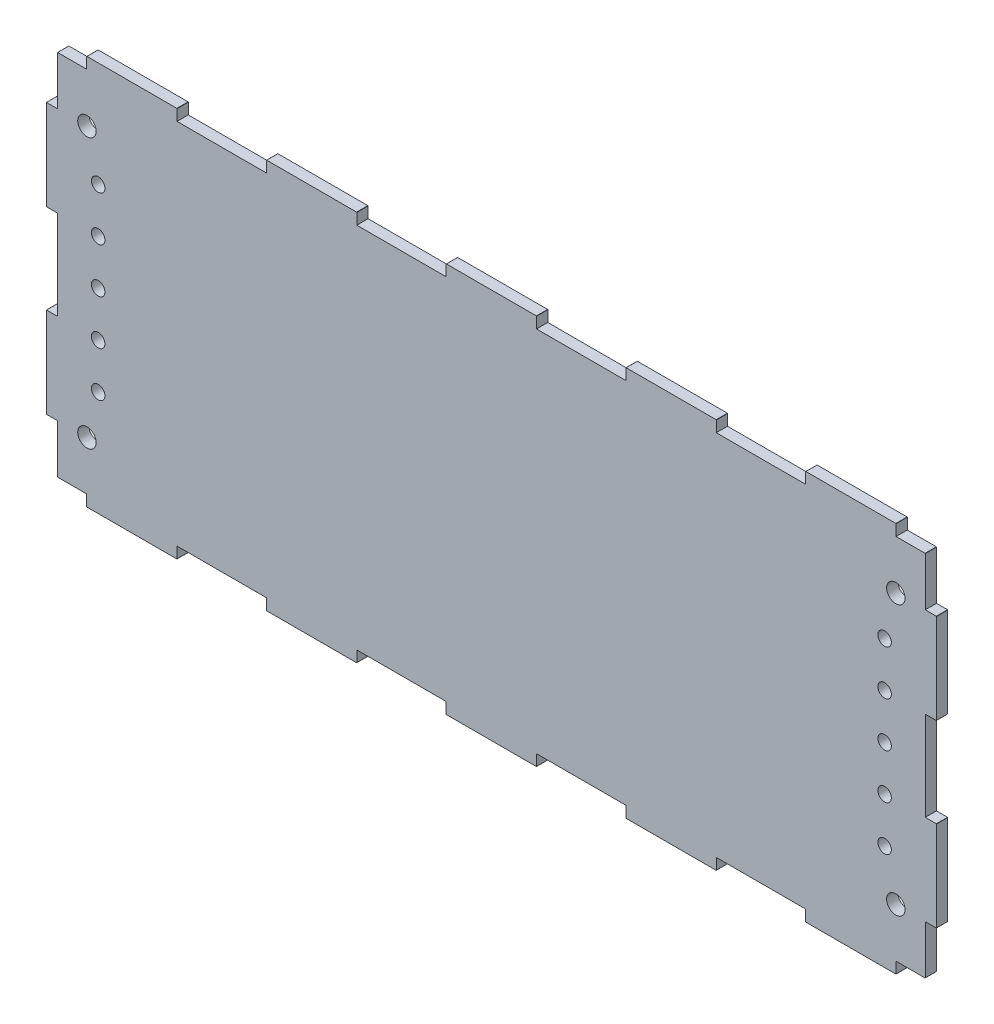
SolidWorks part; units mm, degrees
material "Acrylic (Medium-high impact)"
ref_plane "Front Plane" through (0, 0, 0) normal (0, 0, 1) x (1, 0, 0)
ref_plane "Top Plane" through (0, 0, 0) normal (0, 1, 0) x (1, 0, 0)
ref_plane "Right Plane" through (0, 0, 0) normal (1, 0, 0) x (0, 0, -1)
sketch "Model" plane through (0, 0, 0) normal (0, 0, 1) x (1, 0, 0)
  line L0 (-139.94, -86.83) -> (-139.93, -86.82)
  line L1 (-139.93, -86.82) -> (-139.92, -86.8)
  line L2 (-139.92, -86.8) -> (-139.91, -86.79)
  line L3 (-139.91, -86.79) -> (-139.9, -86.77)
  line L4 (-139.9, -86.77) -> (-139.9, -81.85)
  line L5 (-139.9, -81.85) -> (-100.1, -81.85)
  line L6 (-100.1, -81.85) -> (-100.1, -86.77)
  line L7 (-100.1, -86.77) -> (-100.08, -86.81)
  line L8 (-100.08, -86.81) -> (-100.07, -86.82)
  line L9 (-100.07, -86.82) -> (-100.05, -86.83)
  line L10 (-100.05, -86.83) -> (-100.04, -86.84)
  line L11 (-100.04, -86.84) -> (-100.02, -86.85)
  line L12 (-100.02, -86.85) -> (-59.98, -86.85)
  line L13 (-59.98, -86.85) -> (-59.94, -86.83)
  line L14 (-59.94, -86.83) -> (-59.93, -86.82)
  line L15 (-59.93, -86.82) -> (-59.92, -86.8)
  line L16 (-59.92, -86.8) -> (-59.91, -86.79)
  line L17 (-59.91, -86.79) -> (-59.9, -86.77)
  line L18 (-59.9, -86.77) -> (-59.9, -81.85)
  line L19 (-59.9, -81.85) -> (-20.1, -81.85)
  line L20 (-20.1, -81.85) -> (-20.1, -86.77)
  line L21 (-20.1, -86.77) -> (-20.08, -86.81)
  line L22 (-20.08, -86.81) -> (-20.07, -86.82)
  line L23 (-20.07, -86.82) -> (-20.05, -86.83)
  line L24 (-20.05, -86.83) -> (-20.04, -86.84)
  line L25 (-20.04, -86.84) -> (-20.02, -86.85)
  line L26 (-20.02, -86.85) -> (20.02, -86.85)
  line L27 (20.02, -86.85) -> (20.06, -86.83)
  line L28 (20.06, -86.83) -> (20.07, -86.82)
  line L29 (20.07, -86.82) -> (20.08, -86.8)
  line L30 (20.08, -86.8) -> (20.09, -86.79)
  line L31 (20.09, -86.79) -> (20.1, -86.77)
  line L32 (20.1, -86.77) -> (20.1, -81.85)
  line L33 (20.1, -81.85) -> (59.9, -81.85)
  line L34 (59.9, -81.85) -> (59.9, -86.77)
  line L35 (59.9, -86.77) -> (59.92, -86.81)
  line L36 (59.92, -86.81) -> (59.93, -86.82)
  line L37 (59.93, -86.82) -> (59.95, -86.83)
  line L38 (59.95, -86.83) -> (59.96, -86.84)
  line L39 (59.96, -86.84) -> (59.98, -86.85)
  line L40 (59.98, -86.85) -> (100.02, -86.85)
  line L41 (100.02, -86.85) -> (100.06, -86.83)
  line L42 (100.06, -86.83) -> (100.07, -86.82)
  line L43 (100.07, -86.82) -> (100.08, -86.8)
  line L44 (100.08, -86.8) -> (100.09, -86.79)
  line L45 (100.09, -86.79) -> (100.1, -86.77)
  line L46 (100.1, -86.77) -> (100.1, -81.85)
  line L47 (100.1, -81.85) -> (139.9, -81.85)
  line L48 (139.9, -81.85) -> (139.9, -86.77)
  line L49 (139.9, -86.77) -> (139.92, -86.81)
  line L50 (139.92, -86.81) -> (139.93, -86.82)
  line L51 (139.93, -86.82) -> (139.95, -86.83)
  line L52 (139.95, -86.83) -> (139.96, -86.84)
  line L53 (139.96, -86.84) -> (139.98, -86.85)
  line L54 (139.98, -86.85) -> (180.02, -86.85)
  line L55 (180.02, -86.85) -> (180.06, -86.83)
  line L56 (180.06, -86.83) -> (180.07, -86.82)
  line L57 (180.07, -86.82) -> (180.08, -86.8)
  line L58 (180.08, -86.8) -> (180.09, -86.79)
  line L59 (180.09, -86.79) -> (180.1, -86.77)
  line L60 (180.1, -86.77) -> (180.1, -81.85)
  line L61 (180.1, -81.85) -> (193.02, -81.85)
  line L62 (193.02, -81.85) -> (193.06, -81.83)
  line L63 (193.06, -81.83) -> (193.07, -81.82)
  line L64 (193.07, -81.82) -> (193.08, -81.8)
  line L65 (193.08, -81.8) -> (193.09, -81.79)
  line L66 (193.09, -81.79) -> (193.1, -81.77)
  line L67 (193.1, -81.77) -> (193.1, -60.1)
  line L68 (193.1, -60.1) -> (198.02, -60.1)
  line L69 (198.02, -60.1) -> (198.06, -60.08)
  line L70 (198.06, -60.08) -> (198.07, -60.07)
  line L71 (198.07, -60.07) -> (198.08, -60.05)
  line L72 (198.08, -60.05) -> (198.09, -60.04)
  line L73 (198.09, -60.04) -> (198.1, -60.02)
  line L74 (198.1, -60.02) -> (198.1, -19.98)
  line L75 (198.1, -19.98) -> (198.08, -19.94)
  line L76 (198.08, -19.94) -> (198.07, -19.93)
  line L77 (198.07, -19.93) -> (198.05, -19.92)
  line L78 (198.05, -19.92) -> (198.04, -19.91)
  line L79 (198.04, -19.91) -> (198.02, -19.9)
  line L80 (198.02, -19.9) -> (193.1, -19.9)
  line L81 (193.1, -19.9) -> (193.1, 19.9)
  line L82 (193.1, 19.9) -> (198.02, 19.9)
  line L83 (198.02, 19.9) -> (198.06, 19.92)
  line L84 (198.06, 19.92) -> (198.07, 19.93)
  line L85 (198.07, 19.93) -> (198.08, 19.95)
  line L86 (198.08, 19.95) -> (198.09, 19.96)
  line L87 (198.09, 19.96) -> (198.1, 19.98)
  line L88 (198.1, 19.98) -> (198.1, 60.02)
  line L89 (198.1, 60.02) -> (198.08, 60.06)
  line L90 (198.08, 60.06) -> (198.07, 60.07)
  line L91 (198.07, 60.07) -> (198.05, 60.08)
  line L92 (198.05, 60.08) -> (198.04, 60.09)
  line L93 (198.04, 60.09) -> (198.02, 60.1)
  line L94 (198.02, 60.1) -> (193.1, 60.1)
  line L95 (193.1, 60.1) -> (193.1, 81.77)
  line L96 (193.1, 81.77) -> (193.08, 81.81)
  line L97 (193.08, 81.81) -> (193.07, 81.82)
  line L98 (193.07, 81.82) -> (193.05, 81.83)
  line L99 (193.05, 81.83) -> (193.04, 81.84)
  line L100 (193.04, 81.84) -> (193.02, 81.85)
  line L101 (193.02, 81.85) -> (180.1, 81.85)
  line L102 (180.1, 81.85) -> (180.1, 86.77)
  line L103 (180.1, 86.77) -> (180.08, 86.81)
  line L104 (180.08, 86.81) -> (180.07, 86.82)
  line L105 (180.07, 86.82) -> (180.05, 86.83)
  line L106 (180.05, 86.83) -> (180.04, 86.84)
  line L107 (180.04, 86.84) -> (180.02, 86.85)
  line L108 (180.02, 86.85) -> (139.98, 86.85)
  line L109 (139.98, 86.85) -> (139.94, 86.83)
  line L110 (139.94, 86.83) -> (139.93, 86.82)
  line L111 (139.93, 86.82) -> (139.92, 86.8)
  line L112 (139.92, 86.8) -> (139.91, 86.79)
  line L113 (139.91, 86.79) -> (139.9, 86.77)
  line L114 (139.9, 86.77) -> (139.9, 81.85)
  line L115 (139.9, 81.85) -> (100.1, 81.85)
  line L116 (100.1, 81.85) -> (100.1, 86.77)
  line L117 (100.1, 86.77) -> (100.08, 86.81)
  line L118 (100.08, 86.81) -> (100.07, 86.82)
  line L119 (100.07, 86.82) -> (100.05, 86.83)
  line L120 (100.05, 86.83) -> (100.04, 86.84)
  line L121 (100.04, 86.84) -> (100.02, 86.85)
  line L122 (100.02, 86.85) -> (59.98, 86.85)
  line L123 (59.98, 86.85) -> (59.94, 86.83)
  line L124 (59.94, 86.83) -> (59.93, 86.82)
  line L125 (59.93, 86.82) -> (59.92, 86.8)
  line L126 (59.92, 86.8) -> (59.91, 86.79)
  line L127 (59.91, 86.79) -> (59.9, 86.77)
  line L128 (59.9, 86.77) -> (59.9, 81.85)
  line L129 (59.9, 81.85) -> (20.1, 81.85)
  line L130 (20.1, 81.85) -> (20.1, 86.77)
  line L131 (20.1, 86.77) -> (20.08, 86.81)
  line L132 (20.08, 86.81) -> (20.07, 86.82)
  line L133 (20.07, 86.82) -> (20.05, 86.83)
  line L134 (20.05, 86.83) -> (20.04, 86.84)
  line L135 (20.04, 86.84) -> (20.02, 86.85)
  line L136 (20.02, 86.85) -> (-20.02, 86.85)
  line L137 (-20.02, 86.85) -> (-20.06, 86.83)
  line L138 (-20.06, 86.83) -> (-20.07, 86.82)
  line L139 (-20.07, 86.82) -> (-20.08, 86.8)
  line L140 (-20.08, 86.8) -> (-20.09, 86.79)
  line L141 (-20.09, 86.79) -> (-20.1, 86.77)
  line L142 (-20.1, 86.77) -> (-20.1, 81.85)
  line L143 (-20.1, 81.85) -> (-59.9, 81.85)
  line L144 (-59.9, 81.85) -> (-59.9, 86.77)
  line L145 (-59.9, 86.77) -> (-59.92, 86.81)
  line L146 (-59.92, 86.81) -> (-59.93, 86.82)
  line L147 (-59.93, 86.82) -> (-59.95, 86.83)
  line L148 (-59.95, 86.83) -> (-59.96, 86.84)
  line L149 (-59.96, 86.84) -> (-59.98, 86.85)
  line L150 (-59.98, 86.85) -> (-100.02, 86.85)
  line L151 (-100.02, 86.85) -> (-100.06, 86.83)
  line L152 (-100.06, 86.83) -> (-100.07, 86.82)
  line L153 (-100.07, 86.82) -> (-100.08, 86.8)
  line L154 (-100.08, 86.8) -> (-100.09, 86.79)
  line L155 (-100.09, 86.79) -> (-100.1, 86.77)
  line L156 (-100.1, 86.77) -> (-100.1, 81.85)
  line L157 (-100.1, 81.85) -> (-139.9, 81.85)
  line L158 (-139.9, 81.85) -> (-139.9, 86.77)
  line L159 (-139.9, 86.77) -> (-139.92, 86.81)
  line L160 (-139.92, 86.81) -> (-139.93, 86.82)
  line L161 (-139.93, 86.82) -> (-139.95, 86.83)
  line L162 (-139.95, 86.83) -> (-139.96, 86.84)
  line L163 (-139.96, 86.84) -> (-139.98, 86.85)
  line L164 (-139.98, 86.85) -> (-180.02, 86.85)
  line L165 (-180.02, 86.85) -> (-180.06, 86.83)
  line L166 (-180.06, 86.83) -> (-180.07, 86.82)
  line L167 (-180.07, 86.82) -> (-180.08, 86.8)
  line L168 (-180.08, 86.8) -> (-180.09, 86.79)
  line L169 (-180.09, 86.79) -> (-180.1, 86.77)
  line L170 (-180.1, 86.77) -> (-180.1, 81.85)
  line L171 (-180.1, 81.85) -> (-193.02, 81.85)
  line L172 (-193.02, 81.85) -> (-193.06, 81.83)
  line L173 (-193.06, 81.83) -> (-193.07, 81.82)
  line L174 (-193.07, 81.82) -> (-193.08, 81.8)
  line L175 (-193.08, 81.8) -> (-193.09, 81.79)
  line L176 (-193.09, 81.79) -> (-193.1, 81.77)
  line L177 (-193.1, 81.77) -> (-193.1, 60.1)
  line L178 (-193.1, 60.1) -> (-198.02, 60.1)
  line L179 (-198.02, 60.1) -> (-198.06, 60.08)
  line L180 (-198.06, 60.08) -> (-198.07, 60.07)
  line L181 (-198.07, 60.07) -> (-198.08, 60.05)
  line L182 (-198.08, 60.05) -> (-198.09, 60.04)
  line L183 (-198.09, 60.04) -> (-198.1, 60.02)
  line L184 (-198.1, 60.02) -> (-198.1, 19.98)
  line L185 (-198.1, 19.98) -> (-198.08, 19.94)
  line L186 (-198.08, 19.94) -> (-198.07, 19.93)
  line L187 (-198.07, 19.93) -> (-198.05, 19.92)
  line L188 (-198.05, 19.92) -> (-198.04, 19.91)
  line L189 (-198.04, 19.91) -> (-198.02, 19.9)
  line L190 (-198.02, 19.9) -> (-193.1, 19.9)
  line L191 (-193.1, 19.9) -> (-193.1, -19.9)
  line L192 (-193.1, -19.9) -> (-198.02, -19.9)
  line L193 (-198.02, -19.9) -> (-198.06, -19.92)
  line L194 (-198.06, -19.92) -> (-198.07, -19.93)
  line L195 (-198.07, -19.93) -> (-198.08, -19.95)
  line L196 (-198.08, -19.95) -> (-198.09, -19.96)
  line L197 (-198.09, -19.96) -> (-198.1, -19.98)
  line L198 (-198.1, -19.98) -> (-198.1, -60.02)
  line L199 (-198.1, -60.02) -> (-198.08, -60.06)
  line L200 (-198.08, -60.06) -> (-198.07, -60.07)
  line L201 (-198.07, -60.07) -> (-198.05, -60.08)
  line L202 (-198.05, -60.08) -> (-198.04, -60.09)
  line L203 (-198.04, -60.09) -> (-198.02, -60.1)
  line L204 (-198.02, -60.1) -> (-193.1, -60.1)
  line L205 (-193.1, -60.1) -> (-193.1, -81.77)
  line L206 (-193.1, -81.77) -> (-193.08, -81.81)
  line L207 (-193.08, -81.81) -> (-193.07, -81.82)
  line L208 (-193.07, -81.82) -> (-193.05, -81.83)
  line L209 (-193.05, -81.83) -> (-193.04, -81.84)
  line L210 (-193.04, -81.84) -> (-193.02, -81.85)
  line L211 (-193.02, -81.85) -> (-180.1, -81.85)
  line L212 (-180.1, -81.85) -> (-180.1, -86.77)
  line L213 (-180.1, -86.77) -> (-180.08, -86.81)
  line L214 (-180.08, -86.81) -> (-180.07, -86.82)
  line L215 (-180.07, -86.82) -> (-180.05, -86.83)
  line L216 (-180.05, -86.83) -> (-180.04, -86.84)
  line L217 (-180.04, -86.84) -> (-180.02, -86.85)
  line L218 (-180.02, -86.85) -> (-139.98, -86.85)
  line L219 (-139.98, -86.85) -> (-139.94, -86.83)
extrude "Boss-Extrude1" add sketch "Model" along normal blind 5
sketch "Sketch2" plane through (0, 0, 5) normal (0, 0, 1) x (1, 0, 0)
  line L0 (0, 0) -> (0, 86) construction
  line L1 (0, 86) -> (175, 86) construction
  line L2 (0, 86) -> (-175, 86) construction
  line L3 (-175, 86) -> (-175, -86) construction
  line L4 (-175, -86) -> (175, -86) construction
  line L5 (175, -86) -> (175, 86) construction
  line L6 (-180, 60) -> (0, 60) construction
  line L7 (180, 60) -> (0, 60) construction
  line L8 (180, 60) -> (180, -60) construction
  line L9 (-180, 60) -> (-180, -60) construction
  line L10 (-198.1, 60.02) -> (-198.1, 19.98) construction
  line L11 (198.1, 19.98) -> (198.1, 60.02) construction
  circle A0 centre (-175, 0) radius 3
  circle A1 centre (175, 0) radius 3
  circle A2 centre (-175, 20) radius 3
  circle A3 centre (175, 20) radius 3
  circle A4 centre (-175, 40) radius 3
  circle A5 centre (175, 40) radius 3
  circle A6 centre (-180, 60) radius 4.1
  circle A7 centre (180, 60) radius 4.1
  circle A8 centre (-175, -20) radius 3
  circle A9 centre (175, -20) radius 3
  circle A10 centre (-175, -40) radius 3
  circle A11 centre (175, -40) radius 3
  circle A12 centre (-180, -60) radius 4.1
  circle A13 centre (180, -60) radius 4.1
  dimension "D3" = 6
  dimension "D4" = 6
  dimension "D5" = 8.2
  dimension "D6" = 8.2
  dimension "D7" = 8.2
  dimension "D8" = 8.2
  dimension "D9" = 6
  dimension "D10" = 6
  dimension "D11" = 6
  dimension "D12" = 6
  dimension "D13" = 6
  dimension "D14" = 6
  dimension "D15" = 6
  dimension "D16" = 6
  dimension "D1" = 175
  dimension "D2" = 175
  dimension "D17" = 180
  dimension "D18" = 180
  dimension "D19" = 18.1
  dimension "D20" = 18.1
extrude "Cut-Extrude1" cut sketch "Sketch2" against normal through all
